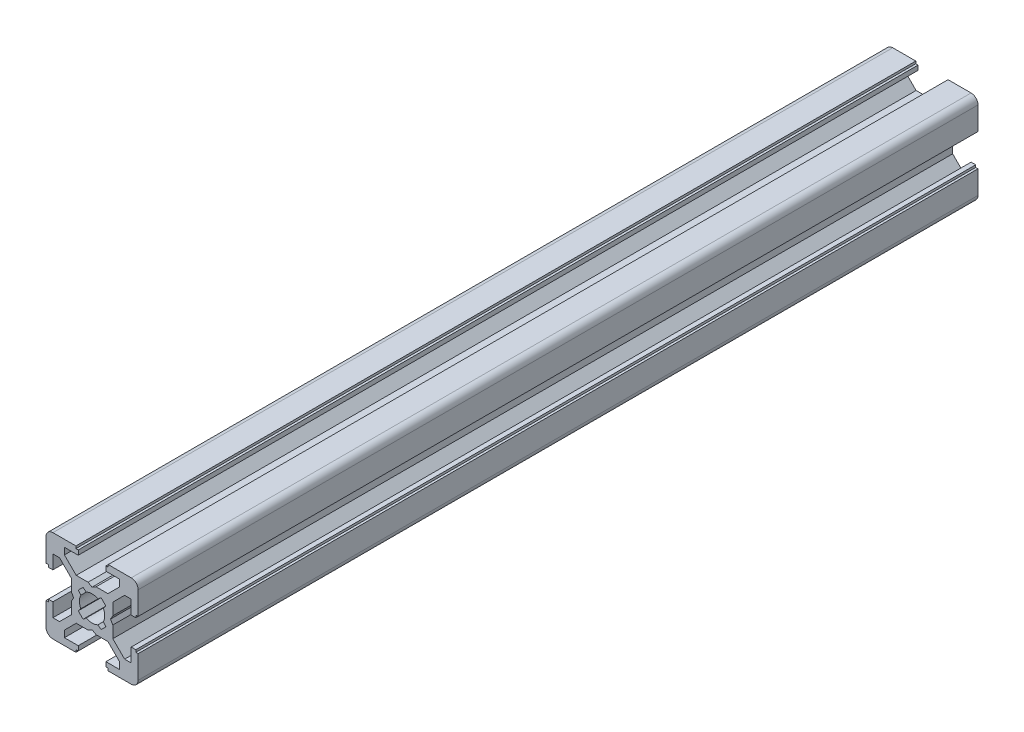
SolidWorks part; units mm, degrees
material "Alliage 1060"
ref_plane "Plan de face" through (0, 0, 0) normal (0, 0, 1) x (1, 0, 0)
ref_plane "Plan de dessus" through (0, 0, 0) normal (0, 1, 0) x (1, 0, 0)
ref_plane "Plan de droite" through (0, 0, 0) normal (1, 0, 0) x (0, 0, -1)
sketch "Esquisse1" plane through (0, 0, 0) normal (0, 0, 1) x (1, 0, 0)
  line L0 (0, 0) -> (-4, 0) construction
  line L1 (-4, 0) -> (-4.5, 0.866)
  line L2 (-4, 0) -> (-4.5, -0.866)
  line L15 (-4.5, 0.866) -> (-4.5, 3.4393)
  line L16 (-4.5, 3.4393) -> (-7.0607, 6)
  line L17 (-7.0607, 6) -> (-8.5, 6)
  line L18 (-8.5, 6) -> (-8.5, 3)
  line L19 (-8.5, 3) -> (-9.5, 3)
  line L20 (-9.5, 3) -> (-9.5, 3.5)
  line L21 (-9.5, 3.5) -> (-10, 3.5)
  line L22 (-10, 3.5) -> (-10, 8.5)
  line L23 (0, 0) -> (0, 1.2745) construction
  line L24 (10, -3.5) -> (10, -8.5)
  line L25 (4.5, -3.4393) -> (7.0607, -6)
  line L26 (-9.5, -3.5) -> (-10, -3.5)
  line L27 (-9.5, -3) -> (-9.5, -3.5)
  line L28 (-8.5, -3) -> (-9.5, -3)
  line L29 (-8.5, -6) -> (-8.5, -3)
  line L30 (-7.0607, -6) -> (-8.5, -6)
  line L31 (-4.5, -0.866) -> (-4.5, -3.4393)
  line L32 (-4.5, -3.4393) -> (-7.0607, -6)
  line L33 (-10, -3.5) -> (-10, -8.5)
  line L34 (4.5, -0.866) -> (4.5, -3.4393)
  line L35 (7.0607, -6) -> (8.5, -6)
  line L36 (8.5, -6) -> (8.5, -3)
  line L37 (8.5, -3) -> (9.5, -3)
  line L38 (9.5, -3) -> (9.5, -3.5)
  line L39 (9.5, -3.5) -> (10, -3.5)
  line L40 (10, 3.5) -> (10, 8.5)
  line L41 (9.5, 3.5) -> (10, 3.5)
  line L42 (9.5, 3) -> (9.5, 3.5)
  line L43 (8.5, 3) -> (9.5, 3)
  line L44 (8.5, 6) -> (8.5, 3)
  line L45 (7.0607, 6) -> (8.5, 6)
  line L46 (4.5, 3.4393) -> (7.0607, 6)
  line L47 (4.5, 0.866) -> (4.5, 3.4393)
  line L48 (4, 0) -> (4.5, -0.866)
  line L49 (4, 0) -> (4.5, 0.866)
  line L50 (3.5, 10) -> (8.5, 10)
  line L51 (3.5, 9.5) -> (3.5, 10)
  line L52 (3, 8.5) -> (3, 9.5)
  line L53 (3, 9.5) -> (3.5, 9.5)
  line L54 (6, 8.5) -> (3, 8.5)
  line L55 (6, 7.0607) -> (6, 8.5)
  line L56 (3.4393, 4.5) -> (6, 7.0607)
  line L57 (0.866, 4.5) -> (3.4393, 4.5)
  line L58 (-0.866, 4.5) -> (-3.4393, 4.5)
  line L59 (-3.4393, 4.5) -> (-6, 7.0607)
  line L60 (-6, 7.0607) -> (-6, 8.5)
  line L61 (-6, 8.5) -> (-3, 8.5)
  line L62 (-3, 8.5) -> (-3, 9.5)
  line L63 (-3, 9.5) -> (-3.5, 9.5)
  line L64 (-3.5, 9.5) -> (-3.5, 10)
  line L65 (-3.5, 10) -> (-8.5, 10)
  line L67 (9.5, -3.5) -> (10, -3.5)
  line L68 (8.5, -3) -> (9.5, -3)
  line L69 (9.5, -3) -> (9.5, -3.5)
  line L70 (8.5, -6) -> (8.5, -3)
  line L71 (7.0607, -6) -> (8.5, -6)
  line L72 (4.5, -3.4393) -> (7.0607, -6)
  line L73 (4.5, -0.866) -> (4.5, -3.4393)
  line L74 (4.5, 0.866) -> (4.5, 3.4393)
  line L75 (4.5, 3.4393) -> (7.0607, 6)
  line L76 (7.0607, 6) -> (8.5, 6)
  line L77 (8.5, 6) -> (8.5, 3)
  line L78 (8.5, 3) -> (9.5, 3)
  line L79 (9.5, 3) -> (9.5, 3.5)
  line L80 (9.5, 3.5) -> (10, 3.5)
  line L82 (-3.5, -10) -> (-8.5, -10)
  line L83 (-3.5, -9.5) -> (-3.5, -10)
  line L84 (-3, -8.5) -> (-3, -9.5)
  line L85 (-3, -9.5) -> (-3.5, -9.5)
  line L86 (-6, -8.5) -> (-3, -8.5)
  line L87 (-6, -7.0607) -> (-6, -8.5)
  line L88 (-3.4393, -4.5) -> (-6, -7.0607)
  line L89 (-0.866, -4.5) -> (-3.4393, -4.5)
  line L90 (0.866, -4.5) -> (3.4393, -4.5)
  line L91 (3.4393, -4.5) -> (6, -7.0607)
  line L92 (6, -7.0607) -> (6, -8.5)
  line L93 (6, -8.5) -> (3, -8.5)
  line L94 (3, -8.5) -> (3, -9.5)
  line L95 (3, -9.5) -> (3.5, -9.5)
  line L96 (3.5, -9.5) -> (3.5, -10)
  line L97 (3.5, -10) -> (8.5, -10)
  line L98 (0, 4) -> (0.866, 4.5)
  line L99 (0, 4) -> (-0.866, 4.5)
  line L100 (4, 0) -> (4.5, -0.866)
  line L101 (4, 0) -> (4.5, 0.866)
  line L102 (0, -4) -> (-0.866, -4.5)
  line L103 (0, -4) -> (0.866, -4.5)
  line L104 (0, 0) -> (-1.9445, 1.9445) construction
  line L105 (10, 3.5) -> (10, 10) [skipped]
  line L106 (10, -3.5) -> (10, -10) [skipped]
  arc A0 (-10, 8.5) -> (-8.5, 10) centre (-8.5, 8.5) cw
  arc A1 (-10, -8.5) -> (-8.5, -10) centre (-8.5, -8.5) ccw
  arc A2 (10, -8.5) -> (8.5, -10) centre (8.5, -8.5) cw
  arc A3 (10, 8.5) -> (8.5, 10) centre (8.5, 8.5) ccw
  circle A4 centre (0, 0) radius 2.75
  point P43 (-10, 10)
  point P98 (0, 0)
  point P101 (-10, -10)
  point P102 (10, -10)
  point P106 (0, 0)
  point P107 (10, 10)
  point P109 (-5.7803, 4.7197)
  dimension "D15" = 1.5
  dimension "D16" = 1.5
  dimension "D14" = 1.5
  dimension "D17" = 5.5
  dimension "D2" = 120
  dimension "D3" = 1
  dimension "D5" = 20
  dimension "D6" = 6
  dimension "D7" = 12
  dimension "D8" = 135
  dimension "D9" = 5.5
  dimension "D10" = 4
  dimension "D11" = 0.5
  dimension "D12" = 4
  dimension "D13" = 0.5
  dimension "D18" = 4
  dimension "D19" = 4.5
  dimension "D4" = 1.5
extrude "Boss.-Extru.1" add sketch "Esquisse1" against normal blind 182.28 contours A1 L82 L83 L85 L84 L86 L87 L88 L89 L102 L103 L90 L91 L92 L93 L94 L95 L96 L97 A2 L24 L39 L38 L37 L36 L35 L25 L34 L48 L49 L47 L46 L45 L44 L43 L42 L41 L40 A3 L50 L51 L53 L52 L54 L55 L56 L57 L98 L99 L58 L59 L60 L61 L62 L63 L64 L65 A0 L22 L21 L20 L19 L18 L17 L16 L15 L1 L2 L31 L32 L30 L29 L28 L27 L26 L33
sketch "Esquisse2" plane through (0, 0, 0) normal (0, 0, 1) x (1, 0, 0)
  line L0 (1.9496, 3.0009) -> (1.2763, 2.4359)
  line L2 (-3.0009, 1.9496) -> (-2.4359, 1.2763)
  line L3 (-1.9473, 3.0032) -> (-1.2732, 2.4375)
  line L4 (-3.0009, 1.9496) -> (-1.9473, 3.0032)
  line L5 (1.9496, 3.0009) -> (3.0032, 1.9473)
  line L6 (3.0032, 1.9473) -> (2.4375, 1.2732)
  line L7 (3.0009, -1.9496) -> (2.4359, -1.2763)
  line L8 (3.0009, -1.9496) -> (1.9473, -3.0032)
  line L9 (1.9473, -3.0032) -> (1.2732, -2.4375)
  line L10 (-1.9496, -3.0009) -> (-1.2763, -2.4359)
  line L11 (-1.9496, -3.0009) -> (-3.0032, -1.9473)
  line L12 (-3.0032, -1.9473) -> (-2.4375, -1.2732)
  line L13 (0, 0) -> (0.8524, 0) construction
  arc A0 (-2.4359, 1.2763) -> (-2.4375, -1.2732) centre (0, 0) ccw
  arc A1 (1.2763, 2.4359) -> (-1.2732, 2.4375) centre (0, 0) ccw
  arc A2 (2.4359, -1.2763) -> (2.4375, 1.2732) centre (0, 0) ccw
  arc A3 (-1.2763, -2.4359) -> (1.2732, -2.4375) centre (0, 0) ccw
  point P7 (-2.4749, 2.4749)
  point P22 (0, 0)
  dimension "D1" = 5.5
  dimension "D2" = 1.49
  dimension "D3" = 95
  dimension "D4" = 0.8789
  dimension "D5" = 95
  dimension "D6" = 0.88
  dimension "D8" = 45
  dimension "D7" = 4
extrude "Enlèv. mat.-Extru.1" cut sketch "Esquisse2" against normal through all
sketch "Esquisse3" plane through (0, 0, 0) normal (0, 0, 1) x (1, 0, 0)
  line L0 (-3.0009, 1.9496) -> (-2.4359, 1.2763) construction
  line L1 (-2.4375, -1.2732) -> (-3.0032, -1.9473) construction
  line L2 (-3.0032, -1.9473) -> (-1.9496, -3.0009) construction
  line L3 (-1.9496, -3.0009) -> (-1.2763, -2.4359) construction
  line L4 (1.2732, -2.4375) -> (1.9473, -3.0032) construction
  line L5 (1.9473, -3.0032) -> (3.0009, -1.9496) construction
  line L6 (3.0009, -1.9496) -> (2.4359, -1.2763) construction
  line L7 (2.4375, 1.2732) -> (3.0032, 1.9473) construction
  line L8 (3.0032, 1.9473) -> (1.9496, 3.0009) construction
  line L9 (1.9496, 3.0009) -> (1.2763, 2.4359) construction
  line L10 (-1.2732, 2.4375) -> (-1.9473, 3.0032) construction
  line L11 (-1.9473, 3.0032) -> (-3.0009, 1.9496) construction
  line L12 (-3.0009, 1.9496) -> (-2.4359, 1.2763)
  line L13 (-2.4375, -1.2732) -> (-3.0032, -1.9473)
  line L14 (-3.0032, -1.9473) -> (-1.9496, -3.0009)
  line L15 (-1.9496, -3.0009) -> (-1.2763, -2.4359)
  line L16 (1.2732, -2.4375) -> (1.9473, -3.0032)
  line L17 (1.9473, -3.0032) -> (3.0009, -1.9496)
  line L18 (3.0009, -1.9496) -> (2.4359, -1.2763)
  line L19 (2.4375, 1.2732) -> (3.0032, 1.9473)
  line L20 (3.0032, 1.9473) -> (1.9496, 3.0009)
  line L21 (1.9496, 3.0009) -> (1.2763, 2.4359)
  line L22 (-1.2732, 2.4375) -> (-1.9473, 3.0032)
  line L23 (-1.9473, 3.0032) -> (-3.0009, 1.9496)
  line L72 (-10, -3.5) -> (-10, -8.5)
  line L73 (-8.5, -10) -> (-3.5, -10)
  line L74 (-3.5, -10) -> (-3.5, -9.5)
  line L75 (-3.5, -9.5) -> (-3, -9.5)
  line L76 (-3, -9.5) -> (-3, -8.5)
  line L77 (-3, -8.5) -> (-6, -8.5)
  line L78 (-6, -8.5) -> (-6, -7.0607)
  line L79 (-6, -7.0607) -> (-3.4393, -4.5)
  line L80 (-3.4393, -4.5) -> (-0.866, -4.5)
  line L81 (-0.866, -4.5) -> (0, -4)
  line L82 (0, -4) -> (0.866, -4.5)
  line L83 (0.866, -4.5) -> (3.4393, -4.5)
  line L84 (3.4393, -4.5) -> (6, -7.0607)
  line L85 (6, -7.0607) -> (6, -8.5)
  line L86 (6, -8.5) -> (3, -8.5)
  line L87 (3, -8.5) -> (3, -9.5)
  line L88 (3, -9.5) -> (3.5, -9.5)
  line L89 (3.5, -9.5) -> (3.5, -10)
  line L90 (3.5, -10) -> (8.5, -10)
  line L91 (10, -8.5) -> (10, -3.5)
  line L92 (10, -3.5) -> (9.5, -3.5)
  line L93 (9.5, -3.5) -> (9.5, -3)
  line L94 (9.5, -3) -> (8.5, -3)
  line L95 (8.5, -3) -> (8.5, -6)
  line L96 (8.5, -6) -> (7.0607, -6)
  line L97 (7.0607, -6) -> (4.5, -3.4393)
  line L98 (4.5, -3.4393) -> (4.5, -0.866)
  line L99 (4.5, -0.866) -> (4, 0)
  line L100 (4, 0) -> (4.5, 0.866)
  line L101 (4.5, 0.866) -> (4.5, 3.4393)
  line L102 (4.5, 3.4393) -> (7.0607, 6)
  line L103 (7.0607, 6) -> (8.5, 6)
  line L104 (8.5, 6) -> (8.5, 3)
  line L105 (8.5, 3) -> (9.5, 3)
  line L106 (9.5, 3) -> (9.5, 3.5)
  line L107 (9.5, 3.5) -> (10, 3.5)
  line L108 (10, 3.5) -> (10, 8.5)
  line L109 (8.5, 10) -> (3.5, 10)
  line L110 (3.5, 10) -> (3.5, 9.5)
  line L111 (3.5, 9.5) -> (3, 9.5)
  line L112 (3, 9.5) -> (3, 8.5)
  line L113 (3, 8.5) -> (6, 8.5)
  line L114 (6, 8.5) -> (6, 7.0607)
  line L115 (6, 7.0607) -> (3.4393, 4.5)
  line L116 (3.4393, 4.5) -> (0.866, 4.5)
  line L117 (0.866, 4.5) -> (0, 4)
  line L118 (0, 4) -> (-0.866, 4.5)
  line L119 (-0.866, 4.5) -> (-3.4393, 4.5)
  line L120 (-3.4393, 4.5) -> (-6, 7.0607)
  line L121 (-6, 7.0607) -> (-6, 8.5)
  line L122 (-6, 8.5) -> (-3, 8.5)
  line L123 (-3, 8.5) -> (-3, 9.5)
  line L124 (-3, 9.5) -> (-3.5, 9.5)
  line L125 (-3.5, 9.5) -> (-3.5, 10)
  line L126 (-3.5, 10) -> (-8.5, 10)
  line L127 (-10, 8.5) -> (-10, 3.5)
  line L128 (-10, 3.5) -> (-9.5, 3.5)
  line L129 (-9.5, 3.5) -> (-9.5, 3)
  line L130 (-9.5, 3) -> (-8.5, 3)
  line L131 (-8.5, 3) -> (-8.5, 6)
  line L132 (-8.5, 6) -> (-7.0607, 6)
  line L133 (-7.0607, 6) -> (-4.5, 3.4393)
  line L134 (-4.5, 3.4393) -> (-4.5, 0.866)
  line L135 (-4.5, 0.866) -> (-4, 0)
  line L136 (-4, 0) -> (-4.5, -0.866)
  line L137 (-4.5, -0.866) -> (-4.5, -3.4393)
  line L138 (-4.5, -3.4393) -> (-7.0607, -6)
  line L139 (-7.0607, -6) -> (-8.5, -6)
  line L140 (-8.5, -6) -> (-8.5, -3)
  line L141 (-8.5, -3) -> (-9.5, -3)
  line L142 (-9.5, -3) -> (-9.5, -3.5)
  line L143 (-9.5, -3.5) -> (-10, -3.5)
  line L144 (-10, -3.5) -> (-10, -8.5)
  line L145 (-8.5, -10) -> (-3.5, -10)
  line L146 (-3.5, -10) -> (-3.5, -9.5)
  line L147 (-3.5, -9.5) -> (-3, -9.5)
  line L148 (-3, -9.5) -> (-3, -8.5)
  line L149 (-3, -8.5) -> (-6, -8.5)
  line L150 (-6, -8.5) -> (-6, -7.0607)
  line L151 (-6, -7.0607) -> (-3.4393, -4.5)
  line L152 (-3.4393, -4.5) -> (-0.866, -4.5)
  line L153 (-0.866, -4.5) -> (0, -4)
  line L154 (0, -4) -> (0.866, -4.5)
  line L155 (0.866, -4.5) -> (3.4393, -4.5)
  line L156 (3.4393, -4.5) -> (6, -7.0607)
  line L157 (6, -7.0607) -> (6, -8.5)
  line L158 (6, -8.5) -> (3, -8.5)
  line L159 (3, -8.5) -> (3, -9.5)
  line L160 (3, -9.5) -> (3.5, -9.5)
  line L161 (3.5, -9.5) -> (3.5, -10)
  line L162 (3.5, -10) -> (8.5, -10)
  line L163 (10, -8.5) -> (10, -3.5)
  line L164 (10, -3.5) -> (9.5, -3.5)
  line L165 (9.5, -3.5) -> (9.5, -3)
  line L166 (9.5, -3) -> (8.5, -3)
  line L167 (8.5, -3) -> (8.5, -6)
  line L168 (8.5, -6) -> (7.0607, -6)
  line L169 (7.0607, -6) -> (4.5, -3.4393)
  line L170 (4.5, -3.4393) -> (4.5, -0.866)
  line L171 (4.5, -0.866) -> (4, 0)
  line L172 (4, 0) -> (4.5, 0.866)
  line L173 (4.5, 0.866) -> (4.5, 3.4393)
  line L174 (4.5, 3.4393) -> (7.0607, 6)
  line L175 (7.0607, 6) -> (8.5, 6)
  line L176 (8.5, 6) -> (8.5, 3)
  line L177 (8.5, 3) -> (9.5, 3)
  line L178 (9.5, 3) -> (9.5, 3.5)
  line L179 (9.5, 3.5) -> (10, 3.5)
  line L180 (10, 3.5) -> (10, 8.5)
  line L181 (8.5, 10) -> (3.5, 10)
  line L182 (3.5, 10) -> (3.5, 9.5)
  line L183 (3.5, 9.5) -> (3, 9.5)
  line L184 (3, 9.5) -> (3, 8.5)
  line L185 (3, 8.5) -> (6, 8.5)
  line L186 (6, 8.5) -> (6, 7.0607)
  line L187 (6, 7.0607) -> (3.4393, 4.5)
  line L188 (3.4393, 4.5) -> (0.866, 4.5)
  line L189 (0.866, 4.5) -> (0, 4)
  line L190 (0, 4) -> (-0.866, 4.5)
  line L191 (-0.866, 4.5) -> (-3.4393, 4.5)
  line L192 (-3.4393, 4.5) -> (-6, 7.0607)
  line L193 (-6, 7.0607) -> (-6, 8.5)
  line L194 (-6, 8.5) -> (-3, 8.5)
  line L195 (-3, 8.5) -> (-3, 9.5)
  line L196 (-3, 9.5) -> (-3.5, 9.5)
  line L197 (-3.5, 9.5) -> (-3.5, 10)
  line L198 (-3.5, 10) -> (-8.5, 10)
  line L199 (-10, 8.5) -> (-10, 3.5)
  line L200 (-10, 3.5) -> (-9.5, 3.5)
  line L201 (-9.5, 3.5) -> (-9.5, 3)
  line L202 (-9.5, 3) -> (-8.5, 3)
  line L203 (-8.5, 3) -> (-8.5, 6)
  line L204 (-8.5, 6) -> (-7.0607, 6)
  line L205 (-7.0607, 6) -> (-4.5, 3.4393)
  line L206 (-4.5, 3.4393) -> (-4.5, 0.866)
  line L207 (-4.5, 0.866) -> (-4, 0)
  line L208 (-4, 0) -> (-4.5, -0.866)
  line L209 (-4.5, -0.866) -> (-4.5, -3.4393)
  line L210 (-4.5, -3.4393) -> (-7.0607, -6)
  line L211 (-7.0607, -6) -> (-8.5, -6)
  line L212 (-8.5, -6) -> (-8.5, -3)
  line L213 (-8.5, -3) -> (-9.5, -3)
  line L214 (-9.5, -3) -> (-9.5, -3.5)
  line L215 (-9.5, -3.5) -> (-10, -3.5)
  arc A0 (-2.4359, 1.2763) -> (-2.4375, -1.2732) centre (0, 0) ccw construction
  arc A1 (-1.2763, -2.4359) -> (1.2732, -2.4375) centre (0, 0) ccw construction
  arc A2 (2.4359, -1.2763) -> (2.4375, 1.2732) centre (0, 0) ccw construction
  arc A3 (1.2763, 2.4359) -> (-1.2732, 2.4375) centre (0, 0) ccw construction
  arc A4 (-10, -8.5) -> (-8.5, -10) centre (-8.5, -8.5) ccw
  arc A5 (8.5, -10) -> (10, -8.5) centre (8.5, -8.5) ccw
  arc A6 (10, 8.5) -> (8.5, 10) centre (8.5, 8.5) ccw
  arc A7 (-8.5, 10) -> (-10, 8.5) centre (-8.5, 8.5) ccw
  arc A8 (-10, -8.5) -> (-8.5, -10) centre (-8.5, -8.5) ccw
  arc A9 (8.5, -10) -> (10, -8.5) centre (8.5, -8.5) ccw
  arc A10 (10, 8.5) -> (8.5, 10) centre (8.5, 8.5) ccw
  arc A11 (-8.5, 10) -> (-10, 8.5) centre (-8.5, 8.5) ccw
  arc A12 (-2.4359, 1.2763) -> (-2.4375, -1.2732) centre (0, 0) ccw
  arc A13 (-1.2763, -2.4359) -> (1.2732, -2.4375) centre (0, 0) ccw
  arc A14 (2.4359, -1.2763) -> (2.4375, 1.2732) centre (0, 0) ccw
  arc A15 (1.2763, 2.4359) -> (-1.2732, 2.4375) centre (0, 0) ccw
  dimension "D1" = 0
